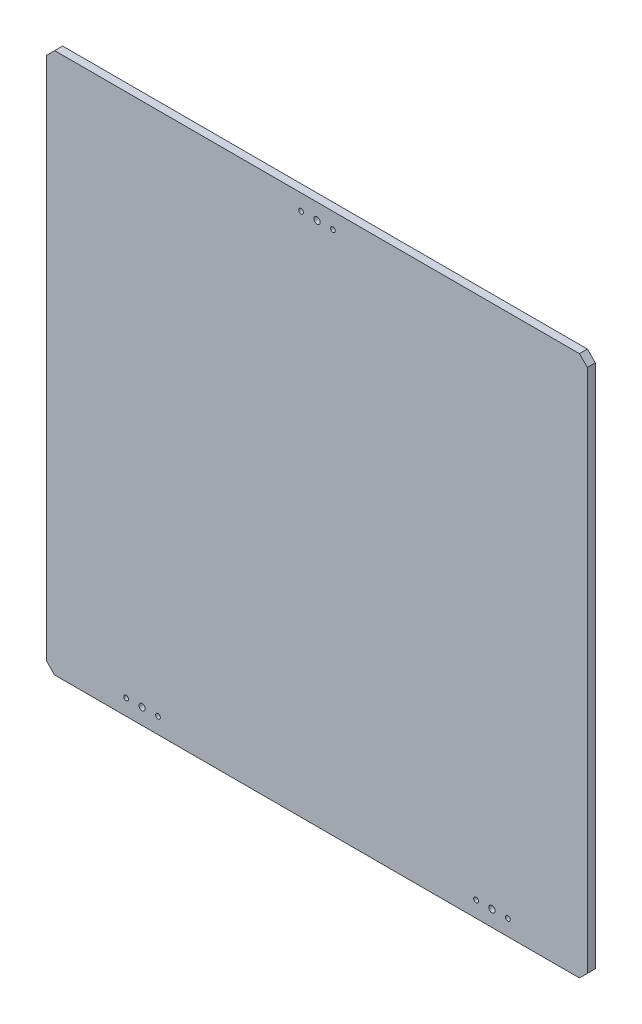
SolidWorks part; units mm, degrees
ref_plane "Front Plane" through (0, 0, 0) normal (0, 0, 1) x (1, 0, 0)
ref_plane "Top Plane" through (0, 0, 0) normal (0, 1, 0) x (1, 0, 0)
ref_plane "Right Plane" through (0, 0, 0) normal (1, 0, 0) x (0, 0, -1)
sketch "Sketch1" plane through (0, 0, 0) normal (0, 0, 1) x (1, 0, 0)
  line L1 (-170, -170) -> (170, -170)
  line L2 (-170, -170) -> (-170, 170)
  line L3 (-170, 170) -> (170, 170)
  line L4 (170, -170) -> (170, 170)
  line L5 (-170, -170) -> (170, 170) construction
  line L6 (-170, 170) -> (170, -170) construction
  point P0 (0, 0)
  dimension "D1" = 340
  dimension "D2" = 340
extrude "Boss-Extrude1" add sketch "Sketch1" along normal blind 5
sketch "Sketch3" plane through (0, 0, 5) normal (0, 0, 1) x (1, 0, 0)
  line L0 (-120, -160) -> (-100, -160) construction
  line L1 (-170, -170) -> (170, -170) construction
  line L2 (-170, -170) -> (-170, 170) construction
  line L3 (-170, 170) -> (170, 170) construction
  line L4 (170, -170) -> (170, 170) construction
  line L5 (-170, -170) -> (170, 170) construction
  line L6 (-170, 170) -> (170, -170) construction
  line L7 (-120, -155) -> (-100, -155) construction
  line L8 (-120, -165) -> (-100, -165) construction
  line L9 (-170, 170) -> (-170, -170) construction
  line L11 (-10, 160) -> (10, 160) construction
  line L12 (0, -55) -> (0, 55) construction
  line L13 (-10, 165) -> (10, 165) construction
  line L14 (-10, 155) -> (10, 155) construction
  arc A0 (-120, -155) -> (-120, -165) centre (-120, -160) ccw construction
  arc A1 (-100, -165) -> (-100, -155) centre (-100, -160) ccw construction
  circle A2 centre (-120, -160) radius 1.5
  circle A3 centre (-110, -160) radius 2
  circle A4 centre (-100, -160) radius 1.5
  arc A5 (-10, 165) -> (-10, 155) centre (-10, 160) ccw construction
  arc A6 (10, 155) -> (10, 165) centre (10, 160) ccw construction
  circle A7 centre (-10, 160) radius 1.5
  circle A8 centre (0, 160) radius 2
  circle A9 centre (10, 160) radius 1.5
  point P0 (0, 0)
  point P8 (-110, -160)
  point P27 (0, 160)
  dimension "D1" = 340
  dimension "D2" = 340
  dimension "D5" = 3
  dimension "D8" = 4
  dimension "D3" = 10
  dimension "D4" = 20
  dimension "D6" = 50
  dimension "D11" = 10
  dimension "D9" = 10
  dimension "D7" = 10
extrude "Cut-Extrude2" cut sketch "Sketch3" against normal through all
mirror "Mirror1" about plane through (0, 0, 0) normal (1, 0, 0) of "Cut-Extrude2"
chamfer "Chamfer1" distance 5 angle 45 4 edges at (-170, -170, 2.5) (170, -170, 2.5) (170, 170, 2.5) (-170, 170, 2.5)
equation "\"table_top_x\"= \"print_bed_x@print_bed.Assembly\""
equation "\"table_top_y\"= \"print_bed_y@print_bed.Assembly\""
equation "\"table_top_z\"= 5"
equation "\"D1@Sketch1\"=\"table_top_x\""
equation "\"D2@Sketch1\"=\"table_top_y\""
equation "\"D1@Boss-Extrude1\"=\"table_top_z\""
equation "\"glass_x\"= \"table_top_x\""
equation "\"glass_y\"= \"table_top_y\""
equation "\"D1@Sketch3\"=\"glass_x\""
equation "\"D2@Sketch3\"=\"glass_y\""
equation "\"D11@Sketch3\"=\"D3@Sketch3\""
equation "\"M3_d\"= \"M3_d@print_bed.Assembly\""
equation "\"M4_d\"= \"M4_d@print_bed.Assembly\""
equation "\"D5@Sketch3\"= \"M3_d\""
equation "\"D8@Sketch3\"=\"M4_d\""
